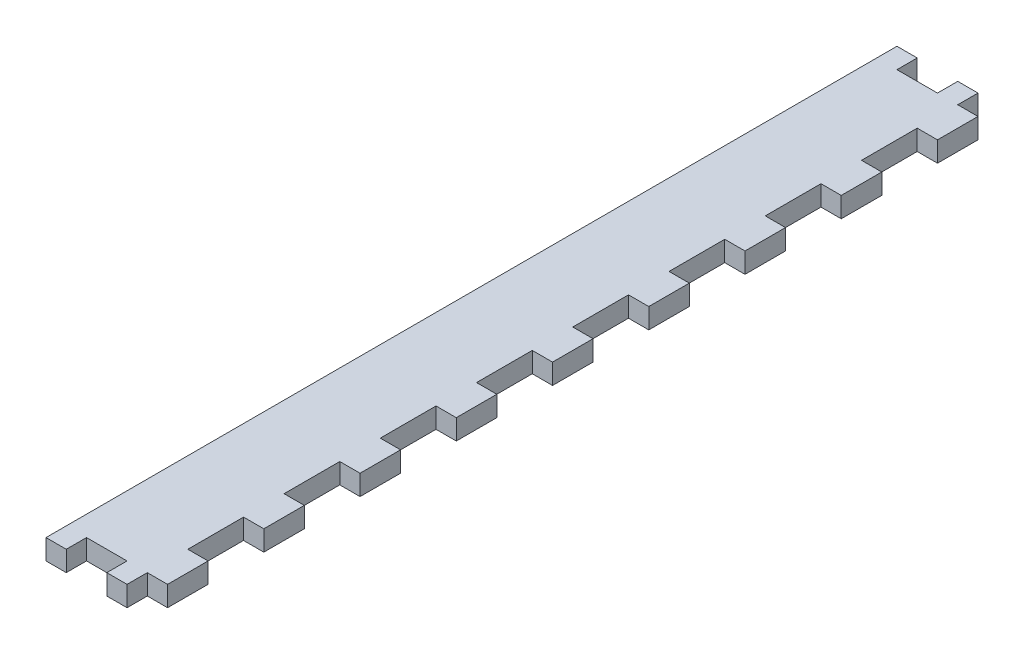
SolidWorks part; units mm, degrees
material "Balsa"
ref_plane "Front Plane" through (0, 0, 0) normal (0, 0, 1) x (1, 0, 0)
ref_plane "Top Plane" through (0, 0, 0) normal (0, 1, 0) x (1, 0, 0)
ref_plane "Right Plane" through (0, 0, 0) normal (1, 0, 0) x (0, 0, -1)
sketch "Sketch1" plane through (0, 0, 0) normal (0, 1, 0) x (1, 0, 0)
  line L1 (0, 0) -> (50.8, 0)
  line L2 (0, 0) -> (0, 533.4)
  line L3 (0, 533.4) -> (50.8, 533.4)
  line L4 (50.8, 0) -> (50.8, 533.4)
  dimension "D1" = 50.8
  dimension "D2" = 533.4
extrude "Boss-Extrude1" add sketch "Sketch1" along normal blind 12.7
sketch "Sketch2" plane through (0, 12.7, 0) normal (0, 1, 0) x (1, 0, 0)
  line L0 (0, 533.4) -> (0, 0) construction
  line L1 (50.8, 495.3) -> (63.5, 495.3)
  line L2 (50.8, 495.3) -> (50.8, 520.7)
  line L3 (0, 520.7) -> (-12.7, 520.7) construction
  line L4 (63.5, 495.3) -> (63.5, 520.7)
  line L5 (50.8, 533.4) -> (0, 533.4) construction
  line L6 (50.8, 434.975) -> (63.5, 434.975)
  line L7 (50.8, 434.975) -> (50.8, 460.375)
  line L8 (50.8, 460.375) -> (63.5, 460.375)
  line L9 (63.5, 434.975) -> (63.5, 460.375)
  line L10 (50.8, 374.65) -> (63.5, 374.65)
  line L11 (50.8, 374.65) -> (50.8, 400.05)
  line L12 (50.8, 400.05) -> (63.5, 400.05)
  line L13 (63.5, 374.65) -> (63.5, 400.05)
  line L14 (50.8, 314.325) -> (63.5, 314.325)
  line L15 (50.8, 314.325) -> (50.8, 339.725)
  line L16 (50.8, 339.725) -> (63.5, 339.725)
  line L17 (63.5, 314.325) -> (63.5, 339.725)
  line L18 (50.8, 254) -> (63.5, 254)
  line L19 (50.8, 254) -> (50.8, 279.4)
  line L20 (50.8, 279.4) -> (63.5, 279.4)
  line L21 (63.5, 254) -> (63.5, 279.4)
  line L22 (50.8, 193.675) -> (63.5, 193.675)
  line L23 (50.8, 193.675) -> (50.8, 219.075)
  line L24 (50.8, 219.075) -> (63.5, 219.075)
  line L25 (63.5, 193.675) -> (63.5, 219.075)
  line L26 (50.8, 133.35) -> (63.5, 133.35)
  line L27 (50.8, 133.35) -> (50.8, 158.75)
  line L28 (50.8, 158.75) -> (63.5, 158.75)
  line L29 (63.5, 133.35) -> (63.5, 158.75)
  line L30 (50.8, 73.025) -> (63.5, 73.025)
  line L31 (50.8, 73.025) -> (50.8, 98.425)
  line L32 (50.8, 98.425) -> (63.5, 98.425)
  line L33 (63.5, 73.025) -> (63.5, 98.425)
  line L34 (-12.7, 12.7) -> (0, 12.7) construction
  line L35 (50.8, 12.7) -> (50.8, 38.1)
  line L36 (50.8, 38.1) -> (63.5, 38.1)
  line L37 (63.5, 12.7) -> (63.5, 38.1)
  line L38 (25.4, 533.4) -> (25.4, 0) construction
  line L39 (0, 0) -> (50.8, 0) construction
  line L40 (-12.7, 12.7) -> (-12.7, 38.1) construction
  line L41 (0, 38.1) -> (-12.7, 38.1) construction
  line L42 (50.8, -47.625) -> (63.5, -47.625) [skipped]
  line L43 (50.8, -47.625) -> (50.8, -22.225) [skipped]
  line L44 (50.8, -22.225) -> (63.5, -22.225) [skipped]
  line L45 (63.5, -47.625) -> (63.5, -22.225) [skipped]
  line L46 (0, 12.7) -> (0, 38.1) construction
  line L47 (50.8, 12.7) -> (63.5, 12.7)
  line L48 (-12.7, 73.025) -> (-12.7, 98.425) construction
  line L49 (0, 98.425) -> (-12.7, 98.425) construction
  line L50 (0, 73.025) -> (0, 98.425) construction
  line L51 (0, 73.025) -> (-12.7, 73.025) construction
  line L52 (-12.7, 133.35) -> (-12.7, 158.75) construction
  line L53 (0, 158.75) -> (-12.7, 158.75) construction
  line L54 (0, 133.35) -> (0, 158.75) construction
  line L55 (0, 133.35) -> (-12.7, 133.35) construction
  line L56 (-12.7, 193.675) -> (-12.7, 219.075) construction
  line L57 (0, 219.075) -> (-12.7, 219.075) construction
  line L58 (0, 193.675) -> (0, 219.075) construction
  line L59 (0, 193.675) -> (-12.7, 193.675) construction
  line L60 (-12.7, 254) -> (-12.7, 279.4) construction
  line L61 (0, 279.4) -> (-12.7, 279.4) construction
  line L62 (0, 254) -> (0, 279.4) construction
  line L63 (0, 254) -> (-12.7, 254) construction
  line L64 (-12.7, 314.325) -> (-12.7, 339.725) construction
  line L65 (0, 339.725) -> (-12.7, 339.725) construction
  line L66 (0, 314.325) -> (0, 339.725) construction
  line L67 (0, 314.325) -> (-12.7, 314.325) construction
  line L68 (-12.7, 374.65) -> (-12.7, 400.05) construction
  line L69 (0, 400.05) -> (-12.7, 400.05) construction
  line L70 (0, 374.65) -> (0, 400.05) construction
  line L71 (0, 374.65) -> (-12.7, 374.65) construction
  line L72 (-12.7, 434.975) -> (-12.7, 460.375) construction
  line L73 (0, 460.375) -> (-12.7, 460.375) construction
  line L74 (0, 434.975) -> (0, 460.375) construction
  line L75 (0, 434.975) -> (-12.7, 434.975) construction
  line L76 (-12.7, 495.3) -> (-12.7, 520.7) construction
  line L77 (50.8, 520.7) -> (63.5, 520.7)
  line L78 (0, 495.3) -> (0, 520.7) construction
  line L79 (0, 495.3) -> (-12.7, 495.3) construction
  line L124 (50.8, 520.7) -> (63.5, 520.7) [skipped]
  line L125 (50.8, 12.7) -> (63.5, 12.7) [skipped]
  dimension "D1" = 25.4
  dimension "D2" = 12.7
  dimension "D3" = 12.7
  dimension "D5" = 12.7
  dimension "D4" = 10
extrude "Boss-Extrude2" add sketch "Sketch2" against normal through all
sketch "Sketch7" plane through (0, 12.7, 0) normal (0, 1, 0) x (1, 0, 0)
  line L0 (25.4, 0) -> (25.4, 533.4) construction
  line L1 (0, 0) -> (50.8, 0) construction
  line L2 (50.8, 533.4) -> (0, 533.4) construction
  line L3 (25.4, 266.7) -> (40.7307, 266.7) construction
  line L4 (12.7, 12.7) -> (38.1, 12.7)
  line L5 (12.7, 12.7) -> (12.7, 0)
  line L6 (12.7, 0) -> (38.1, 0)
  line L7 (38.1, 12.7) -> (38.1, 0)
  line L10 (38.1, 520.7) -> (38.1, 533.4)
  line L11 (12.7, 533.4) -> (38.1, 533.4)
  line L12 (12.7, 520.7) -> (12.7, 533.4)
  line L13 (12.7, 520.7) -> (38.1, 520.7)
  dimension "D1" = 25.4
  dimension "D2" = 12.7
extrude "Cut-Extrude3" cut sketch "Sketch7" against normal through all
